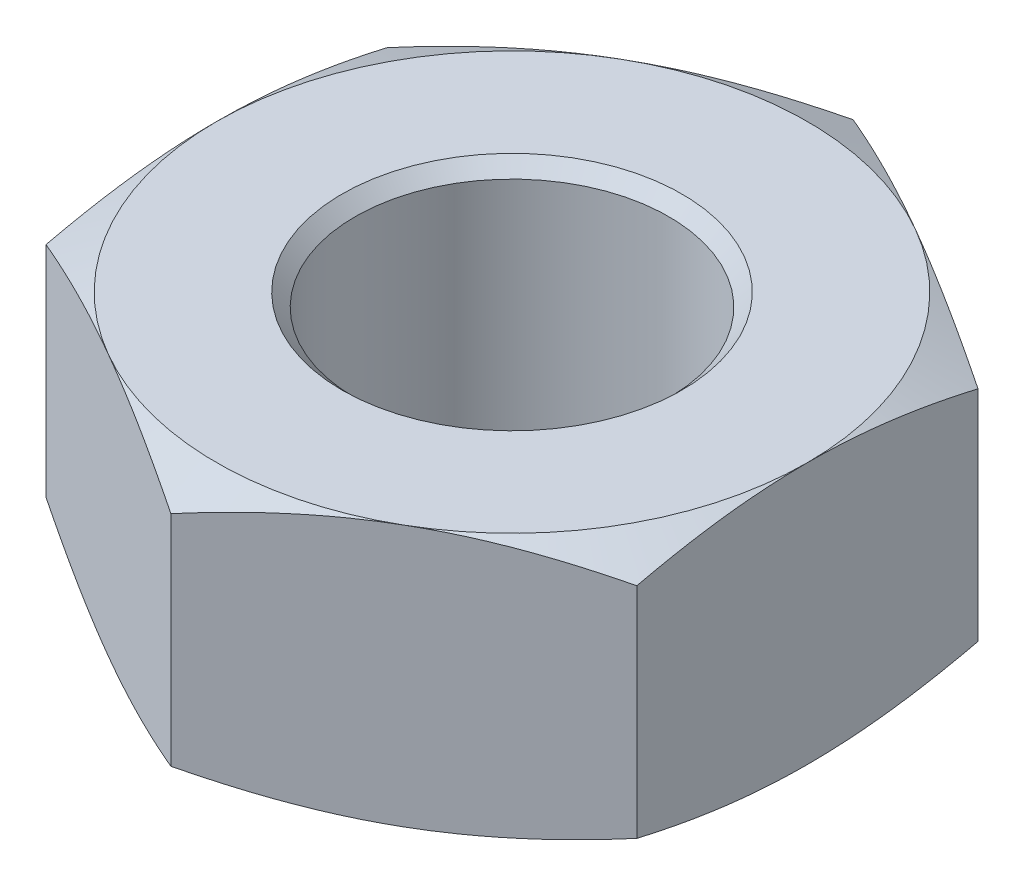
SolidWorks part; units mm, degrees
material "Galvanized Steel"
ref_plane "Front Plane" through (0, 0, 0) normal (0, 0, 1) x (1, 0, 0)
ref_plane "Top Plane" through (0, 0, 0) normal (0, 1, 0) x (1, 0, 0)
ref_plane "Right Plane" through (0, 0, 0) normal (1, 0, 0) x (0, 0, -1)
sketch "Sketch1" plane through (0, 0, 0) normal (0, 1, 0) x (1, 0, 0)
  line L1 (0, 3.9144) -> (-3.39, 1.9572)
  line L2 (-3.39, 1.9572) -> (-3.39, -1.9572)
  line L3 (-3.39, -1.9572) -> (0, -3.9144)
  line L4 (0, -3.9144) -> (3.39, -1.9572)
  line L5 (3.39, -1.9572) -> (3.39, 1.9572)
  line L6 (3.39, 1.9572) -> (0, 3.9144)
  circle A0 centre (0, 0) radius 3.39 construction
  circle A1 centre (0, 0) radius 1.8
  dimension "D2" = 3.6
  dimension "D1" = 6.78
extrude "Boss-Extrude1" add sketch "Sketch1" along normal mid plane 3
chamfer "Chamfer1" distance 0.15 angle 45 2 edges at (0, -1.5, 1.8) (0, 1.5, 1.8)
sketch "Sketch2" plane through (0, 0, 0) normal (0, 0, 1) x (1, 0, 0)
  line L0 (-3.39, 1.5) -> (-5, 0.7492)
  line L1 (-5, 0.7492) -> (-5, 1.5)
  line L2 (-5, 1.5) -> (-3.39, 1.5)
  line L3 (0, 0) -> (0, 3.4047) construction
  dimension "D1" = 5
  dimension "D2" = 25
revolve "Cut-Revolve1" cut sketch "Sketch2" angle 360 about L3
mirror "Mirror1" about plane through (0, 0, 0) normal (0, 1, 0) of "Cut-Revolve1"
